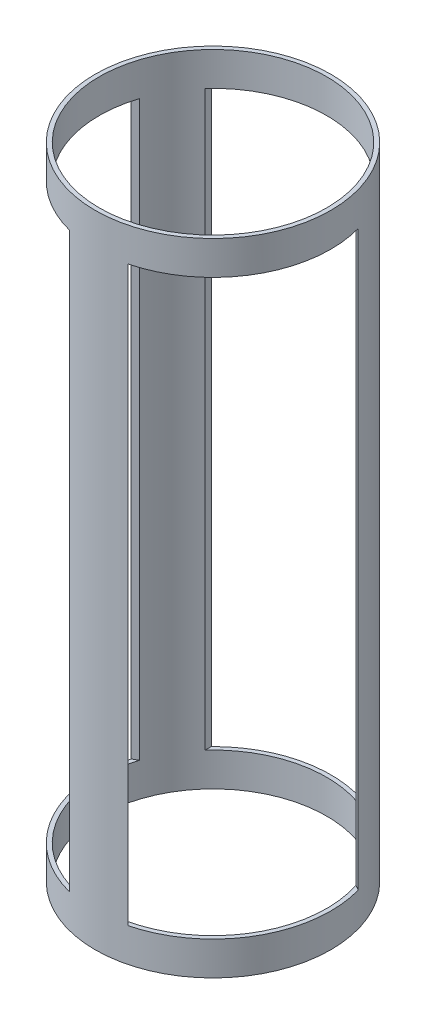
SolidWorks part; units mm, degrees
material "6061-T6 (SS)"
ref_plane "Front Plane" through (0, 0, 0) normal (0, 0, 1) x (1, 0, 0)
ref_plane "Top Plane" through (0, 0, 0) normal (0, 1, 0) x (1, 0, 0)
ref_plane "Right Plane" through (0, 0, 0) normal (1, 0, 0) x (0, 0, -1)
sketch "Sketch1" plane through (0, 0, 0) normal (0, 1, 0) x (1, 0, 0)
  circle A0 centre (0, 0) radius 88.9
  circle A1 centre (0, 0) radius 85.725
  dimension "D1" = 177.8
  dimension "D2" = 171.45
extrude "Boss-Extrude1" add sketch "Sketch1" along normal mid plane 482.854
sketch "Sketch2" plane through (0, 0, 0) normal (0, 0, 1) x (1, 0, 0)
  line L0 (85.725, 241.427) -> (-85.725, 241.427) construction
  line L1 (-63.5, -216.027) -> (63.5, -216.027)
  line L2 (-63.5, -216.027) -> (-63.5, 216.027)
  line L3 (-63.5, 216.027) -> (63.5, 216.027)
  line L4 (63.5, -216.027) -> (63.5, 216.027)
  line L5 (-63.5, -216.027) -> (63.5, 216.027) construction
  line L6 (-63.5, 216.027) -> (63.5, -216.027) construction
  line L7 (88.9, -241.427) -> (88.9, 241.427) construction
  point P0 (0, 0)
  dimension "D1" = 25.4
  dimension "D2" = 25.4
extrude "Cut-Extrude1" cut sketch "Sketch2" against normal up to surface (62.217 mm away)
pattern_circular "CirPattern1" count 3 over 360 about axis through (0, 0, 0) along (0, 1, 0) of "Cut-Extrude1"
ref_plane "Plane1" through (88.9, 0, 0) normal (1, 0, 0) x (0, 0, -1)
sketch "Sketch4" plane through (88.9, 0, 0) normal (1, 0, 0) x (0, 0, -1)
  line L0 (0, 97.79) -> (0, -97.79) construction
  line L1 (88.9, 241.427) -> (-88.9, 241.427) construction
  circle A0 centre (0, 235.077) radius 1.4351
  dimension "D1" = 2.8702
  dimension "D2" = 6.35
extrude "Cut-Extrude3" [suppressed] cut sketch "Sketch4" against normal blind 15.24
pattern_circular "CirPattern3" [suppressed] count 12 over 360
mirror "Mirror1" [suppressed] about plane through (0, 0, 0) normal (0, 1, 0)
ref_plane "Plane2" [suppressed] through (0, 0, 88.9) normal (0, 0, 1) x (1, 0, 0)
sketch "Sketch5" [suppressed] plane through (0, 0, 88.9) normal (0, 0, 1) x (1, 0, 0)
  circle A0 centre (0, 78.359) radius 1.4351
  circle A1 centre (0, -78.359) radius 1.4351
  circle A2 centre (0, -235.077) radius 1.4351 construction
  circle A3 centre (0, 235.077) radius 1.4351 construction
  dimension "D1" = 156.718
  dimension "D2" = 156.718
  dimension "D3" = 2.8702
  dimension "D4" = 2.8702
extrude "Cut-Extrude4" [suppressed] cut sketch "Sketch5" against normal blind 22.86
pattern_circular "CirPattern4" [suppressed] count 3 over 360
